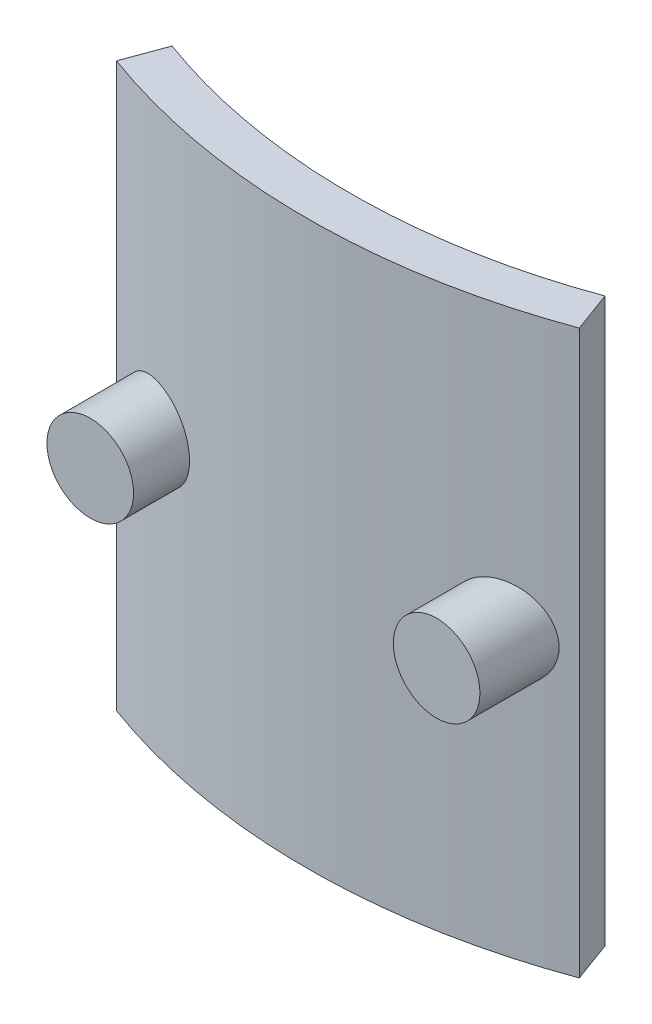
SolidWorks part; units mm, degrees
ref_plane "Front Plane" through (0, 0, 0) normal (0, 0, 1) x (1, 0, 0)
ref_plane "Top Plane" through (0, 0, 0) normal (0, 1, 0) x (1, 0, 0)
ref_plane "Right Plane" through (0, 0, 0) normal (1, 0, 0) x (0, 0, -1)
sketch "Sketch1" plane through (0, 0, 0) normal (0, 1, 0) x (1, 0, 0)
  line L0 (-25, 4.4467) -> (25, 4.4467) construction
  line L1 (-25, 4.4467) -> (-26.7241, -0.2466)
  line L2 (25, 4.4467) -> (26.7241, -0.2466)
  arc A0 (25, 4.4467) -> (-25, 4.4467) centre (0, 72.5) cw
  arc A1 (26.7241, -0.2466) -> (-26.7241, -0.2466) centre (0, 72.5) cw
  dimension "D1" = 72.5
  dimension "D2" = 50
  dimension "D3" = 5
extrude "Boss-Extrude1" add sketch "Sketch1" along normal mid plane 65
sketch "Sketch2" plane through (0, 0, 0) normal (0, 0, 1) x (1, 0, 0)
  line L0 (-20, 0) -> (0, 0) construction
  line L1 (0, 0) -> (20, 0) construction
  circle A0 centre (-20, 0) radius 5
  circle A1 centre (20, 0) radius 5
  dimension "D1" = 10
  dimension "D2" = 20
extrude "Boss-Extrude2" add sketch "Sketch2" along normal blind 10
